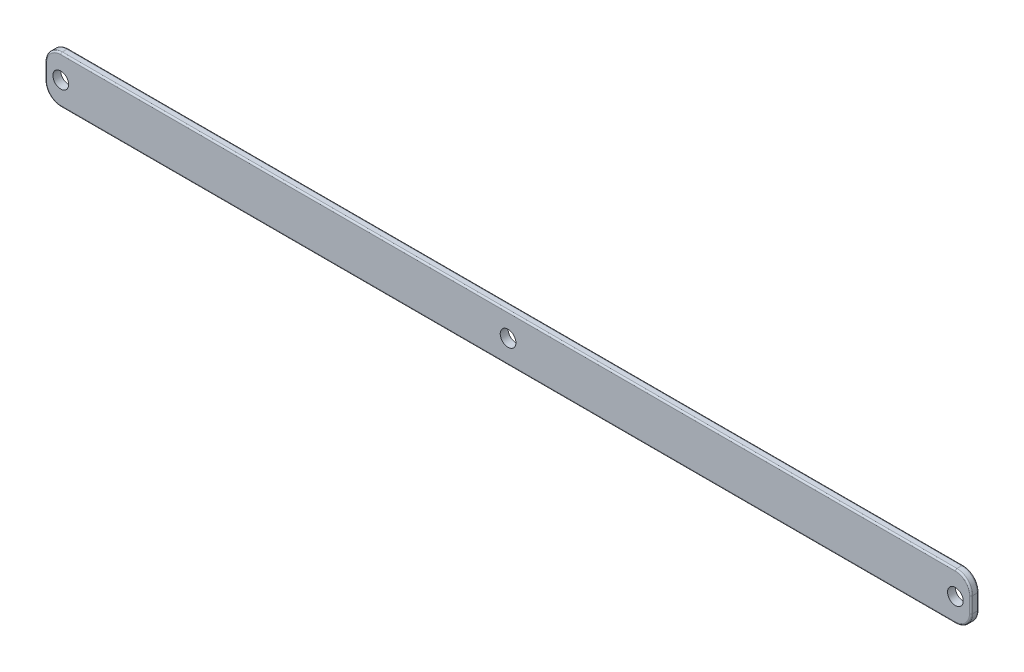
SolidWorks part; units mm, degrees
ref_plane "정면" through (0, 0, 0) normal (0, 0, 1) x (1, 0, 0)
ref_plane "윗면" through (0, 0, 0) normal (0, 1, 0) x (1, 0, 0)
ref_plane "우측면" through (0, 0, 0) normal (1, 0, 0) x (0, 0, -1)
sketch "스케치1" plane through (0, 0, 0) normal (0, 0, 1) x (1, 0, 0)
  line L1 (-289.3224, 55.1673) -> (300.6776, 55.1673)
  line L2 (-289.3224, 55.1673) -> (-289.3224, 25.1673)
  line L3 (-289.3224, 25.1673) -> (300.6776, 25.1673)
  line L4 (300.6776, 55.1673) -> (300.6776, 25.1673)
  circle A0 centre (-279.3224, 40.1673) radius 5
  circle A1 centre (290.6776, 40.1673) radius 5
  circle A2 centre (5.6776, 40.1673) radius 5
  point P11 (300.6776, 40.1673)
  point P12 (5.6776, 25.1673)
  dimension "D3" = 10
  dimension "D4" = 10
  dimension "D5" = 10
  dimension "D1" = 590
  dimension "D2" = 30
  dimension "D6" = 10
  dimension "D7" = 10
extrude "보스-돌출1" add sketch "스케치1" along normal blind 5
fillet "필렛1" radius 10 4 edges at (300.6776, 25.1673, 2.5) (300.6776, 55.1673, 2.5) (-289.3224, 25.1673, 2.5) (-289.3224, 55.1673, 2.5)
fillet "필렛2" radius 1 16 edges at (300.6776, 40.1673, 5) (297.7487, 28.0963, 5) (5.6776, 25.1673, 5) (-286.3935, 28.0963, 5) (-289.3224, 40.1673, 5) (-286.3935, 52.2384, 5) (5.6776, 55.1673, 5) (297.7487, 52.2384, 0) (5.6776, 55.1673, 0) (-286.3935, 52.2384, 0) (-289.3224, 40.1673, 0) (-286.3935, 28.0963, 0) (5.6776, 25.1673, 0) (297.7487, 28.0963, 0) (300.6776, 40.1673, 0) (297.7487, 52.2384, 5)
